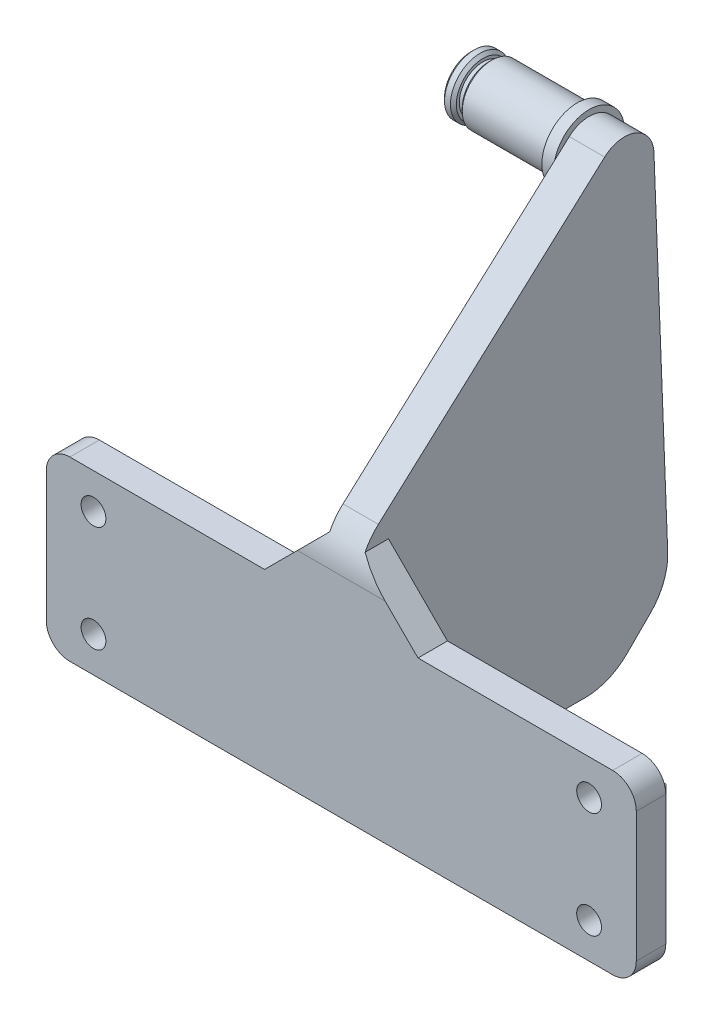
SolidWorks part; units mm, degrees
material "ABS"
ref_plane "Front Plane" through (0, 0, 0) normal (0, 0, 1) x (1, 0, 0)
ref_plane "Top Plane" through (0, 0, 0) normal (0, 1, 0) x (1, 0, 0)
ref_plane "Right Plane" through (0, 0, 0) normal (1, 0, 0) x (0, 0, -1)
sketch "Sketch1" plane through (0, 0, 0) normal (0, 0, 1) x (1, 0, 0)
  line L1 (0, 0) -> (100, 0)
  line L2 (0, 0) -> (0, 30)
  line L3 (0, 30) -> (100, 30)
  line L4 (100, 0) -> (100, 30)
  dimension "D1" = 100
  dimension "D2" = 30
extrude "Boss-Extrude1" add sketch "Sketch1" along normal blind 5 contours L3 L4 L1 L2
sketch "Sketch2" plane through (0, 30, 0) normal (0, 1, 0) x (1, 0, 0)
  line L0 (50, 0) -> (50, -5) construction
  line L1 (0, 0) -> (100, 0) construction
  line L2 (0, -5) -> (100, -5) construction
  line L3 (50, -2.5) -> (65.4254, -2.5) construction
  line L4 (47, 47.5) -> (53, 47.5)
  line L5 (47, 47.5) -> (47, -2.5)
  line L6 (47, -2.5) -> (53, -2.5)
  line L7 (53, 47.5) -> (53, -2.5)
  dimension "D1" = 6
  dimension "D2" = 3
  dimension "D3" = 50
  dimension "D4" = 50
extrude "Boss-Extrude2" add sketch "Sketch2" against normal up to surface (30 mm away) up to face at (50, 0, 2.5)
sketch "Sketch3" plane through (0, 30, 0) normal (0, 1, 0) x (1, 0, 0)
  line L0 (0, -5) -> (100, -5) construction
  line L1 (47, 47.5) -> (53, 47.5)
  line L2 (47, 47.5) -> (47, -5)
  line L3 (47, -5) -> (53, -5)
  line L4 (53, 47.5) -> (53, -5)
extrude "Boss-Extrude3" add sketch "Sketch3" along normal blind 50
sketch "Sketch4" plane through (47, 0, 0) normal (-1, 0, 0) x (0, 0, 1)
  line L1 (-47.5, 80) -> (5, 80) construction
  line L2 (5, 80) -> (5, 30) construction
  circle A0 centre (-40, 74) radius 5
  dimension "D1" = 10
  dimension "D2" = 45
  dimension "D3" = 6
extrude "Boss-Extrude4" add sketch "Sketch4" along normal blind 20
chamfer "Chamfer1" distance 10 angle 45 1 edges at (50, 0, -47.5)
fillet "Fillet1" radius 10 2 edges at (50, 80, 5) (50, 80, -47.5)
chamfer "Chamfer2" distance 10 angle 45 2 edges at (53, 30, 2.5) (47, 30, 2.5)
fillet "Fillet2" radius 4 4 edges at (100, 0, 2.5) (100, 30, 2.5) (0, 0, 2.5) (0, 30, 2.5)
sketch "Sketch5" plane through (0, 0, 0) normal (0, 0, -1) x (-1, 0, 0)
  line L12 (-100, 15) -> (0, 15) construction
  line L13 (-100, 4) -> (-100, 26) construction
  line L14 (0, 4) -> (0, 26) construction
  line L16 (-100, 17.5) -> (0, 17.5)
  line L17 (-100, 17.5) -> (-100, 12.5)
  line L18 (-100, 12.5) -> (0, 12.5)
  line L19 (0, 17.5) -> (0, 12.5)
  dimension "D1" = 5
  dimension "D2" = 2.5
extrude "Boss-Extrude5" add sketch "Sketch5" along normal blind 10
chamfer "Chamfer3" distance 10 angle 45 2 edges at (0, 15, -10) (100, 15, -10)
sketch "Sketch6" plane through (27, 0, 0) normal (-1, 0, 0) x (0, 0, 1)
  circle A0 centre (-40, 74) radius 13
  dimension "D1" = 26
sketch "Sketch7" plane through (0, 0, 0) normal (0, 0, -1) x (-1, 0, 0)
  line L0 (-100, 12.5) -> (-100, 17.5) construction
  line L1 (-92, 24) -> (-8, 24) construction
  line L2 (-92, 24) -> (-92, 6) construction
  line L3 (-92, 6) -> (-8, 6) construction
  line L4 (-8, 24) -> (-8, 6) construction
  line L5 (-63, 30) -> (-96, 30) construction
  line L6 (0, 17.5) -> (0, 12.5) construction
  line L7 (-4, 0) -> (-47, 0) construction
  circle A0 centre (-92, 24) radius 2.1
  circle A1 centre (-8, 24) radius 2.1
  circle A2 centre (-8, 6) radius 2.1
  circle A3 centre (-92, 6) radius 2.1
  dimension "D5" = 4.2
  dimension "D6" = 4.2
  dimension "D7" = 4.2
  dimension "D8" = 4.2
  dimension "D1" = 8
  dimension "D2" = 6
  dimension "D3" = 8
  dimension "D4" = 6
extrude "Cut-Extrude1" cut sketch "Sketch7" against normal through all
sketch "Sketch8" plane through (47, 0, 0) normal (-1, 0, 0) x (0, 0, 1)
  line L0 (-36.644, 77.7064) -> (5, 40)
  line L1 (-44.9962, 74.1949) -> (-47.5, 10)
  line L2 (5, 70) -> (5, 40) construction
  line L3 (-37.5, 80) -> (-5, 80) construction
  line L4 (-47.5, 10) -> (-47.5, 70) construction
  line L5 (5, 70) -> (5, 40)
  line L6 (-37.5, 80) -> (-5, 80)
  line L7 (-47.5, 10) -> (-47.5, 70)
  arc A0 (-36.644, 77.7064) -> (-44.9962, 74.1949) centre (-40, 74) ccw
  arc A1 (5, 70) -> (-5, 80) centre (-5, 70) ccw construction
  arc A2 (-37.5, 80) -> (-47.5, 70) centre (-37.5, 70) ccw construction
  arc A3 (5, 70) -> (-5, 80) centre (-5, 70) ccw
  arc A4 (-37.5, 80) -> (-47.5, 70) centre (-37.5, 70) ccw
  dimension "D1" = 10
extrude "Cut-Extrude2" cut sketch "Sketch8" against normal through all contours L1 L7 A4 L6 A3 L5 L0 A0
fillet "Fillet3" radius 10 3 edges at (50, 40, 5) (50, 0, -37.5) (50, 10, -47.5)
sketch "Sketch9" plane through (47, 0, 0) normal (-1, 0, 0) x (0, 0, 1)
  circle A0 centre (-40, 74) radius 6
  circle A1 centre (-40, 74) radius 5 construction
  dimension "D1" = 1
extrude "Boss-Extrude6" add sketch "Sketch9" along normal blind 2
chamfer "Chamfer4" distance 0.5 angle 45 1 edges at (27, 74, -35)
ref_plane "Plane1" through (30, 0, 0) normal (-1, 0, 0) x (0, 0, 1)
sketch "Sketch10" plane through (30, 0, 0) normal (-1, 0, 0) x (0, 0, 1)
  circle A0 centre (-40, 74) radius 5
  circle A1 centre (-40, 74) radius 4
  dimension "D1" = 10
  dimension "D2" = 1
extrude "Cut-Extrude3" cut sketch "Sketch10" along normal blind 1
chamfer "Chamfer5" distance 0.5 angle 45 2 edges at (29, 74, -35) (30, 74, -35)
